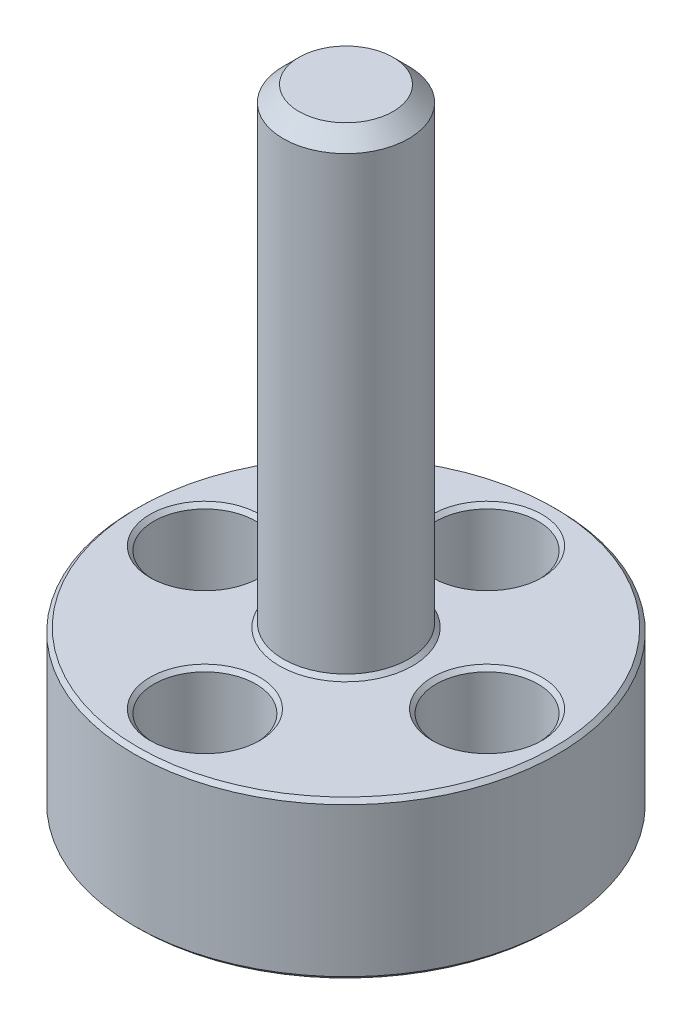
SolidWorks part; units mm, degrees
material "6061 Alloy"
ref_plane "Front Plane" through (0, 0, 0) normal (0, 0, 1) x (1, 0, 0)
ref_plane "Top Plane" through (0, 0, 0) normal (0, 1, 0) x (1, 0, 0)
ref_plane "Right Plane" through (0, 0, 0) normal (1, 0, 0) x (0, 0, -1)
sketch "Sketch2" plane through (0, 0, 0) normal (0, 1, 0) x (1, 0, 0)
  circle A0 centre (0, 0) radius 13.5
  dimension "D1" = 27
extrude "Boss-Extrude1" add sketch "Sketch2" along normal blind 10
sketch "Sketch3" plane through (0, 0, 0) normal (0, 1, 0) x (1, 0, 0)
  circle A0 centre (0, 0) radius 4
  dimension "D1" = 8
extrude "Boss-Extrude2" add sketch "Sketch3" along normal blind 40
cosmetic thread "Cosmetic Thread1" parameters "D1"=25, "D2"=6.619
sketch "Sketch9" plane through (0, 10, 0) normal (0, 1, 0) x (1, 0, 0)
  line L0 (0, 0) -> (-9, 0) construction
  line L2 (0, 0) -> (9, 0) construction
  line L3 (0, 0) -> (0, 9) construction
  line L5 (0, 0) -> (0, -9) construction
  circle A0 centre (0, 0) radius 9 construction
  point P0 (-9, 0)
  point P13 (9, 0)
  point P18 (0, 9)
  point P23 (0, -9)
  point P29 (0, 9)
  point P31 (9, 0)
  point P35 (0, -9)
  dimension "D1" = 18
hole_wizard "CBORE for M3 SHCS1" positions "Sketch9" profile "Sketch8" counterbore size "M3" standard "ANSI Metric" end condition through all
sketch "Sketch8" plane through (-9, 10, 0) normal (1, 0, 0) x (0, 0, 1)
  line L0 (0, 0) -> (0, 10)
  line L1 (0, 10) -> (1.6, 10)
  line L3 (1.6, 10) -> (1.6, 5)
  line L4 (1.6, 5) -> (3.25, 5)
  line L5 (3.25, 5) -> (3.25, 0)
  line L7 (3.25, 0) -> (0, 0)
  line L11 (0, -6.35) -> (0, 107.95) construction
  dimension "Thru Hole Dia." = 3.2
  dimension "Thru Hole Depth" = 10
  dimension "C'Bore Dia." = 6.5
  dimension "C'Bore Depth" = 5
sketch "Sketch10" plane through (0, 0, 0) normal (0, 1, 0) x (1, 0, 0)
  circle A0 centre (0, 0) radius 2.25
  dimension "D1" = 4.5
extrude "Cut-Extrude3" cut sketch "Sketch10" along normal blind 7
chamfer "Chamfer1" distance 0.25 angle 45 12 edges at (0, 0, 13.5) (0, 0, 10.6) (9, 0, 1.6) (0, 0, -7.4) (-9, 0, 1.6) (0, 0, 2.25) (0, 10, 13.5) (0, 10, 4) (0, 10, 12.25) (9, 10, 3.25) (0, 10, -5.75) (-9, 10, 3.25)
chamfer "Chamfer2" distance 1 angle 45 1 edges at (0, 40, 4)
